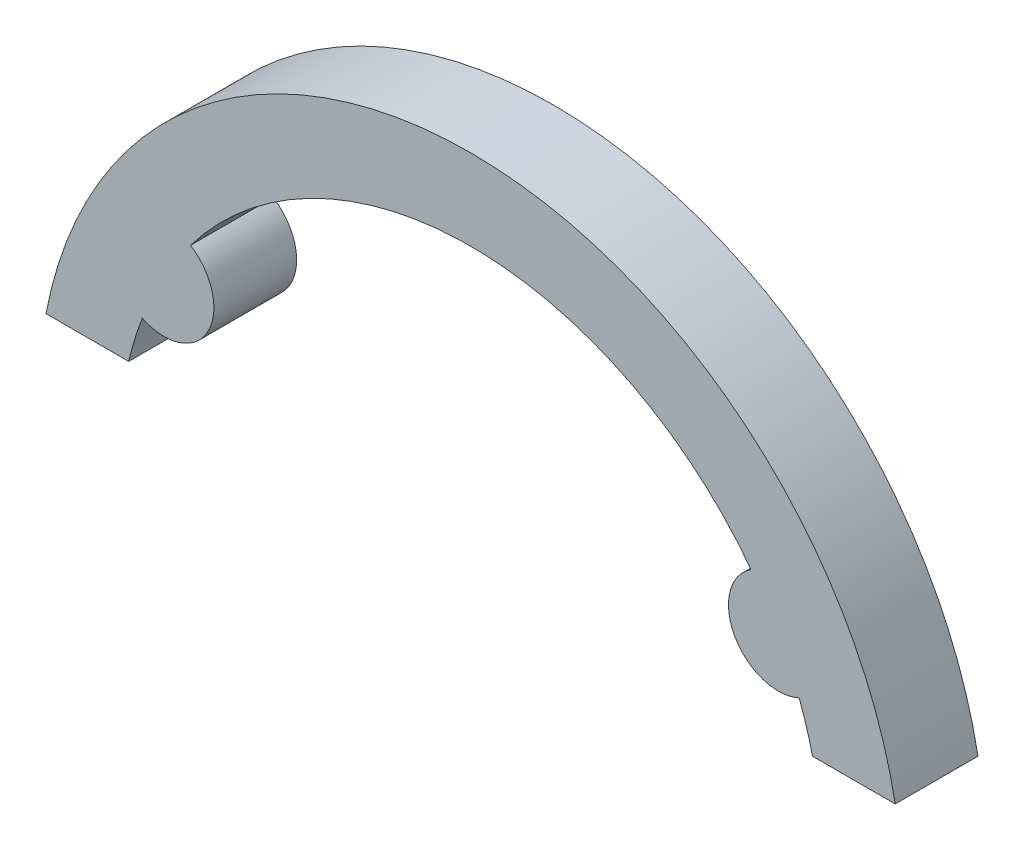
SolidWorks part; units mm, degrees
ref_plane "Front Plane" through (0, 0, 0) normal (0, 0, 1) x (1, 0, 0)
ref_plane "Top Plane" through (0, 0, 0) normal (0, 1, 0) x (1, 0, 0)
ref_plane "Right Plane" through (0, 0, 0) normal (1, 0, 0) x (0, 0, -1)
sketch "Sketch1" plane through (0, 0, 0) normal (0, 0, 1) x (1, 0, 0)
  line L4 (-51.1398, 9.7839) -> (-41.1927, 9.7829)
  line L5 (41.0567, 9.7849) -> (51.0043, 9.7839)
  arc A4 (-51.1398, 9.7839) -> (51.0043, 9.7839) centre (-0.0678, 0.1022) cw
  arc A6 (-33.7645, 25.5877) -> (-39.5644, 15.102) centre (-36.9455, 20.5003) cw
  arc A8 (33.6708, 25.5322) -> (39.4479, 15.0516) centre (36.9467, 20.5054) ccw
  arc A9 (-41.1927, 9.7829) -> (-39.5644, 15.102) centre (-0.0678, 0.1022) cw
  arc A10 (-33.7645, 25.5877) -> (33.6708, 25.5322) centre (-0.0678, 0.1022) cw
  arc A11 (39.4479, 15.0516) -> (41.0567, 9.7849) centre (-0.0678, 0.1022) cw
  point P6 (0, 0)
  point P7 (0.002, 0.0099)
  dimension "D1" = 51.9816
  dimension "D6" = 6
  dimension "D7" = 6
  dimension "D2" = 42.249
  dimension "D9" = 33.6708
extrude "Boss-Extrude6" add sketch "Sketch1" along normal blind 9.9553
